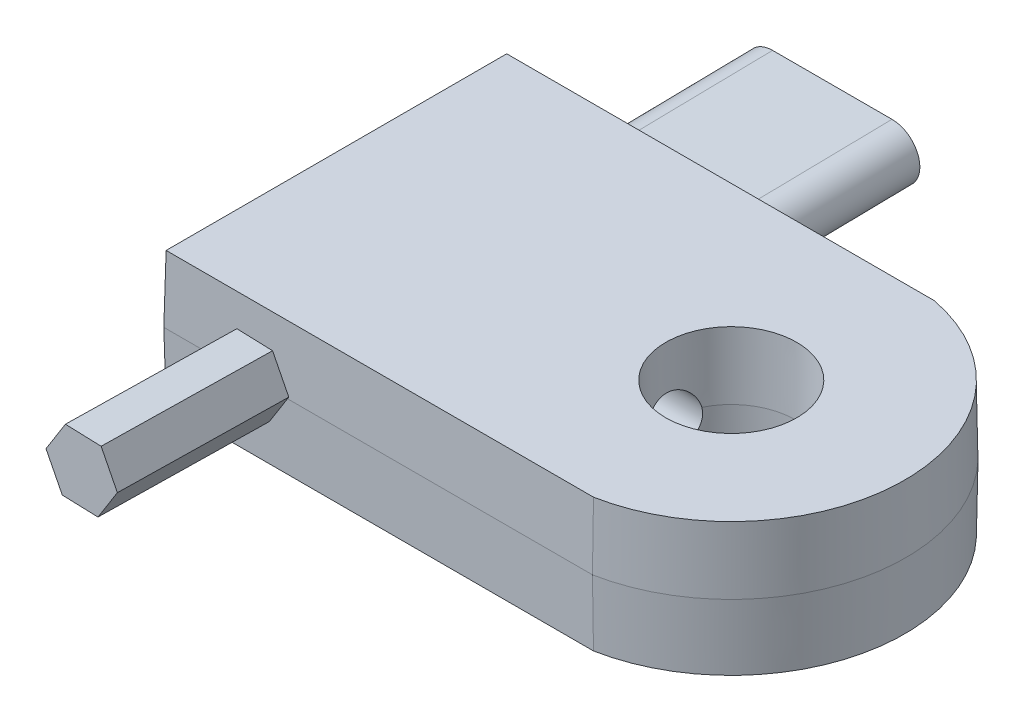
SolidWorks part; units mm, degrees
ref_plane "Front Plane" through (0, 0, 0) normal (0, 0, 1) x (1, 0, 0)
ref_plane "Top Plane" through (0, 0, 0) normal (0, 1, 0) x (1, 0, 0)
ref_plane "Right Plane" through (0, 0, 0) normal (1, 0, 0) x (0, 0, -1)
sketch "Sketch1" plane through (0, 0, 0) normal (0, 1, 0) x (1, 0, 0)
  line L1 (-20.8237, 37.109) -> (79.1763, 37.109)
  line L2 (-20.8237, 37.109) -> (-20.8237, -42.891)
  line L3 (-20.8237, -42.891) -> (79.1763, -42.891)
  arc A0 (79.1763, -42.891) -> (79.1763, 37.109) centre (71.564, -2.891) ccw
  circle A1 centre (71.564, -2.891) radius 15
  dimension "D3" = 30
  dimension "D1" = 100
  dimension "D2" = 80
extrude "Boss-Extrude1" add sketch "Sketch1" along normal mid plane 31.08 draft 1
sketch "Sketch4" plane through (-20.8173, 0.3634, 0) normal (-0.9998, 0.0175, 0) x (0, 0, 1)
  line L0 (-37.109, -0.3634) -> (42.891, -0.3634) construction
  circle A0 centre (2.891, -0.3634) radius 6.7446
extrude "Cut-Extrude3" cut sketch "Sketch4" against normal blind 93.3198
sketch "Sketch5" plane through (0, 0.6475, -37.0977) normal (0, 0.0175, -0.9998) x (-1, 0, 0)
  line L0 (-29.1763, -0.6476) -> (-1.3226, -0.6476) construction
  line L1 (-79.1763, -0.6476) -> (20.8237, -0.6476) construction
  line L2 (-29.1763, 5.7435) -> (-1.3226, 5.7435)
  line L3 (-29.1763, -7.0388) -> (-1.3226, -7.0388)
  arc A0 (-29.1763, 5.7435) -> (-29.1763, -7.0388) centre (-29.1763, -0.6476) ccw
  arc A1 (-1.3226, -7.0388) -> (-1.3226, 5.7435) centre (-1.3226, -0.6476) ccw
  point P4 (-15.2495, -0.6476)
extrude "Boss-Extrude4" add sketch "Sketch5" along normal blind 40
sketch "Sketch6" plane through (0, 0.7484, 42.8779) normal (0, 0.0175, 0.9998) x (1, 0, 0)
  line L1 (3.9221, -7.3564) -> (8.3318, -0.2816)
  line L2 (8.3318, -0.2816) -> (4.4098, 7.0748)
  line L3 (4.4098, 7.0748) -> (-3.9221, 7.3564)
  line L4 (-3.9221, 7.3564) -> (-8.3318, 0.2816)
  line L5 (-8.3318, 0.2816) -> (-4.4098, -7.0748)
  line L6 (-4.4098, -7.0748) -> (3.9221, -7.3564)
  circle A0 centre (0, 0) radius 7.2197 construction
extrude "Boss-Extrude5" add sketch "Sketch6" along normal blind 40
